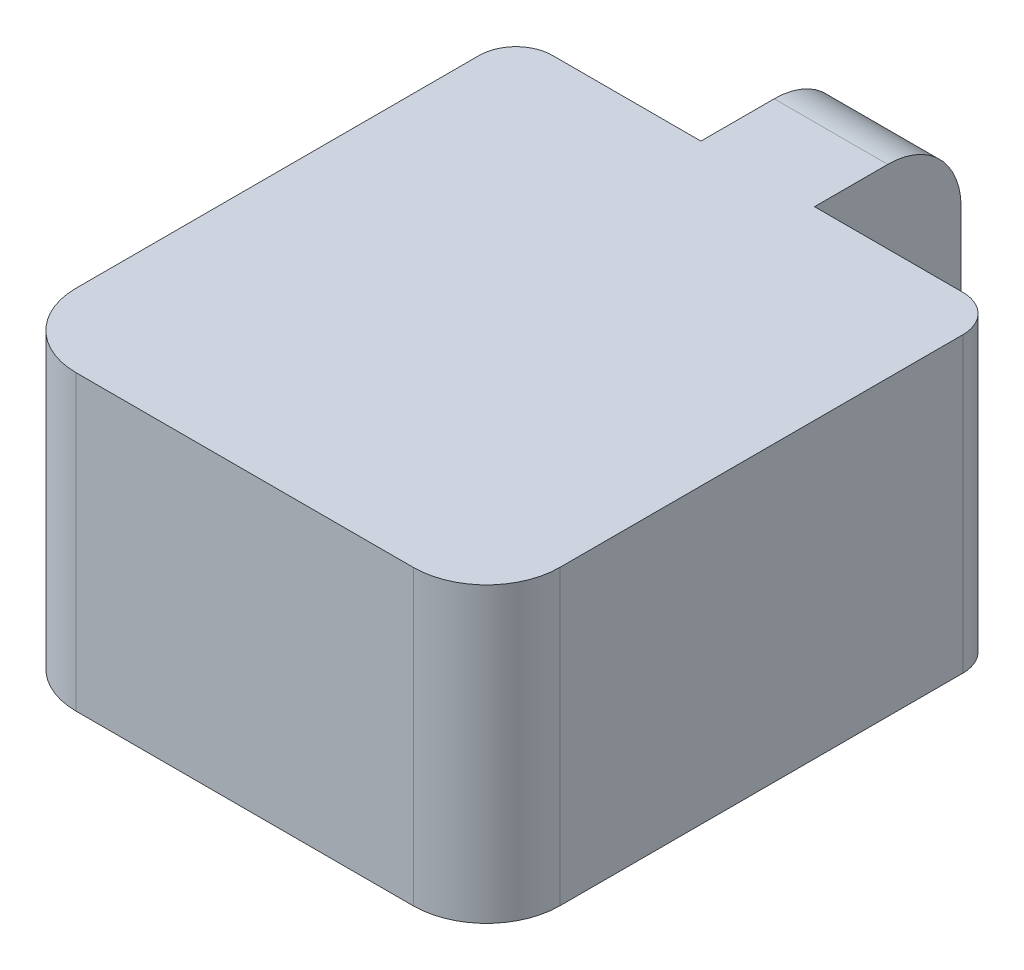
SolidWorks part; units mm, degrees
ref_plane "Front Plane" through (0, 0, 0) normal (0, 0, 1) x (1, 0, 0)
ref_plane "Top Plane" through (0, 0, 0) normal (0, 1, 0) x (1, 0, 0)
ref_plane "Right Plane" through (0, 0, 0) normal (1, 0, 0) x (0, 0, -1)
sketch "Sketch1" plane through (0, 0, 0) normal (0, 1, 0) x (1, 0, 0)
  line L0 (0, 0) -> (0, 12.2427) construction
  line L1 (0, 0) -> (15.5, 0)
  line L2 (15.5, 0) -> (15.5, -20)
  line L3 (15.5, -20) -> (40.75, -20)
  line L4 (40.75, -20) -> (40.75, -90)
  line L5 (40.75, -90) -> (-25.25, -90)
  line L6 (-25.25, -90) -> (-25.25, -20)
  line L7 (-25.25, -20) -> (0, -20)
  line L8 (0, -20) -> (0, 0)
  dimension "D1" = 15.5
  dimension "D2" = 25.25
  dimension "D3" = 25.25
  dimension "D4" = 70
  dimension "D5" = 20
extrude "Boss-Extrude2" add sketch "Sketch1" along normal blind 40
ref_plane "Plane1" through (0, 0, 0) normal (-1, 0, 0) x (0, 0, 1)
sketch "Sketch2" plane through (0, 0, 0) normal (-1, 0, 0) x (0, 0, 1)
  line L0 (0, 0) -> (20, 0) construction
  line L2 (0, 40) -> (0, 0) construction
  circle A0 centre (10, 20) radius 5
  dimension "D1" = 10
  dimension "D2" = 20
  dimension "D3" = 10
fillet "Fillet1" radius 10 1 edges at (7.75, 40, 0)
fillet "Fillet2" radius 10 1 edges at (40.75, 20, 90)
fillet "Fillet3" radius 10 1 edges at (-25.25, 20, 90)
sketch "Sketch3" plane through (0, 0, 0) normal (-1, 0, 0) x (0, 0, 1)
  line L0 (0, 30) -> (0, 0) construction
  line L1 (0, 10) -> (20, 10)
  line L2 (0, 10) -> (0, 0)
  line L3 (0, 0) -> (20, 0)
  line L4 (20, 10) -> (20, 0)
  line L5 (0, 0) -> (20, 0) construction
  line L6 (20, 40) -> (20, 0) construction
  dimension "D1" = 10
extrude "Cut-Extrude2" cut sketch "Sketch3" against normal blind 40
fillet "Fillet4" radius 5 1 edges at (7.75, 10, 0)
fillet "Fillet5" radius 5 1 edges at (-25.25, 20, 20)
fillet "Fillet6" radius 5 1 edges at (40.75, 20, 20)
extrude "Cut-Extrude3" cut sketch "Sketch2" against normal blind 28 contours A0
